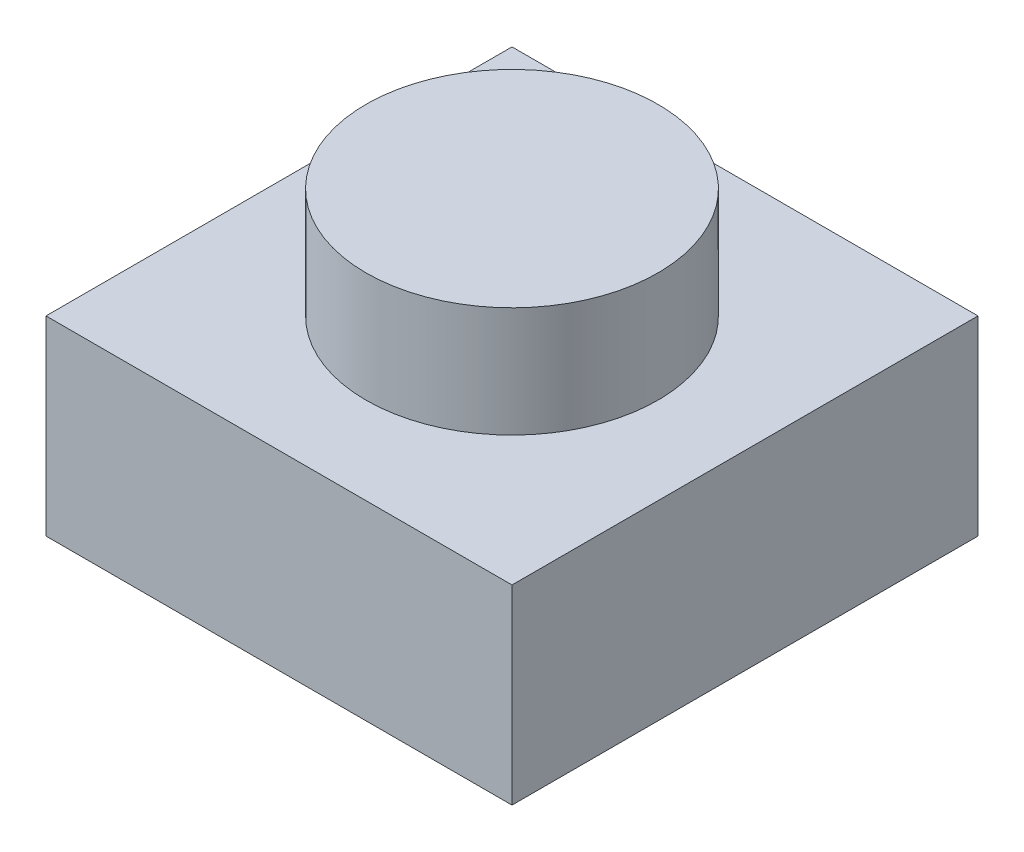
SolidWorks part; units mm, degrees
ref_plane "Front Plane" through (0, 0, 0) normal (0, 0, 1) x (1, 0, 0)
ref_plane "Top Plane" through (0, 0, 0) normal (0, 1, 0) x (1, 0, 0)
ref_plane "Right Plane" through (0, 0, 0) normal (1, 0, 0) x (0, 0, -1)
sketch "Sketch1" plane through (0, 0, 0) normal (0, 1, 0) x (1, 0, 0)
  line L1 (-3.91, 3.91) -> (3.91, 3.91)
  line L2 (-3.91, 3.91) -> (-3.91, -3.91)
  line L3 (-3.91, -3.91) -> (3.91, -3.91)
  line L4 (3.91, 3.91) -> (3.91, -3.91)
  line L5 (-3.91, 3.91) -> (3.91, -3.91) construction
  line L6 (-3.91, -3.91) -> (3.91, 3.91) construction
  point P0 (0, 0)
  dimension "D1" = 7.82
  dimension "D2" = 7.82
extrude "Boss-Extrude1" add sketch "Sketch1" against normal blind 3.2
sketch "Sketch2" plane through (0, 0, 0) normal (0, 1, 0) x (1, 0, 0)
  circle A0 centre (0, 0) radius 2.45
  dimension "D1" = 4.9
extrude "Boss-Extrude2" add sketch "Sketch2" along normal blind 1.85
shell "Shell1" thickness 1.51
